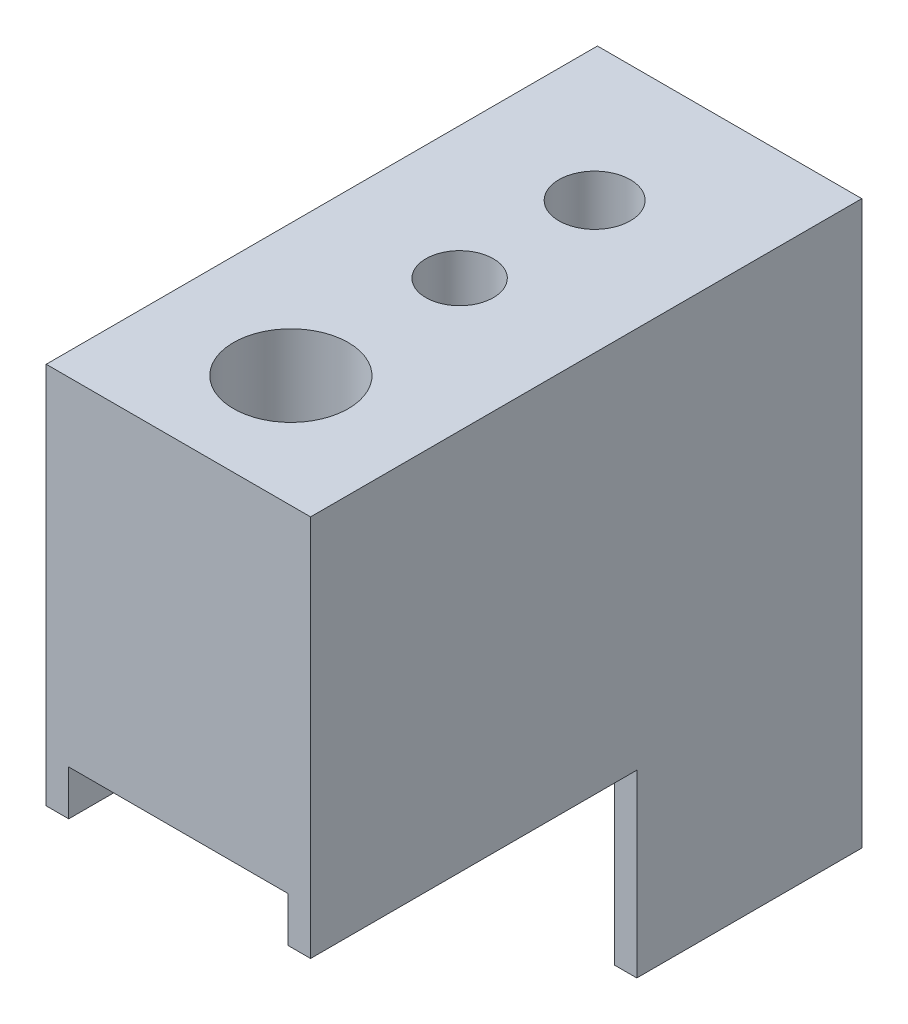
SolidWorks part; units mm, degrees
ref_plane "Front Plane" through (0, 0, 0) normal (0, 0, 1) x (1, 0, 0)
ref_plane "Top Plane" through (0, 0, 0) normal (0, 1, 0) x (1, 0, 0)
ref_plane "Right Plane" through (0, 0, 0) normal (1, 0, 0) x (0, 0, -1)
sketch "Sketch2" plane through (0, 0, 0) normal (1, 0, 0) x (0, 0, -1)
  line L0 (-44, 0) -> (0, 0)
  line L1 (0, 0) -> (0, -20)
  line L2 (-44, 0) -> (-44, 30)
  line L3 (-44, 30) -> (5, 30)
  line L4 (5, 30) -> (5, -20)
  line L5 (5, -20) -> (0, -20)
  dimension "D1" = 20
  dimension "D2" = 44
  dimension "D3" = 5
  dimension "D4" = 30
extrude "Boss-Extrude1" add sketch "Sketch2" along normal mid plane 19.5
sketch "Sketch3" plane through (9.75, 0, 0) normal (1, 0, 0) x (0, 0, -1)
  line L0 (-44, 30) -> (-44, -4)
  line L1 (-44, -4) -> (-15, -4)
  line L2 (-15, -4) -> (-15, -20)
  line L3 (-15, -20) -> (5, -20)
  line L6 (-44, 30) -> (5, 30)
  line L7 (5, 30) -> (5, -20)
  line L8 (0, 0) -> (0, -20) construction
  line L9 (-44, 0) -> (0, 0) construction
  dimension "D1" = 15
  dimension "D2" = 4
extrude "Boss-Extrude2" add sketch "Sketch3" along normal blind 2
mirror "Mirror1" about plane through (0, 0, 0) normal (1, 0, 0) of "Boss-Extrude2"
sketch "Sketch4" plane through (0, 0, 0) normal (0, -1, 0) x (1, 0, 0)
  line L0 (0, 0) -> (0, 7) construction
  line L1 (9.75, 0) -> (-9.75, 0) construction
  line L2 (0, 7) -> (0, 19) construction
  line L3 (0, 19) -> (0, 34) construction
  circle A0 centre (0, 34) radius 5.1
  circle A1 centre (0, 19) radius 3
  circle A2 centre (0, 7) radius 3.175
  dimension "D1" = 10.2
  dimension "D5" = 6
  dimension "D6" = 6.35
  dimension "D2" = 7
  dimension "D3" = 12
  dimension "D4" = 15
extrude "Cut-Extrude1" cut sketch "Sketch4" against normal through all
